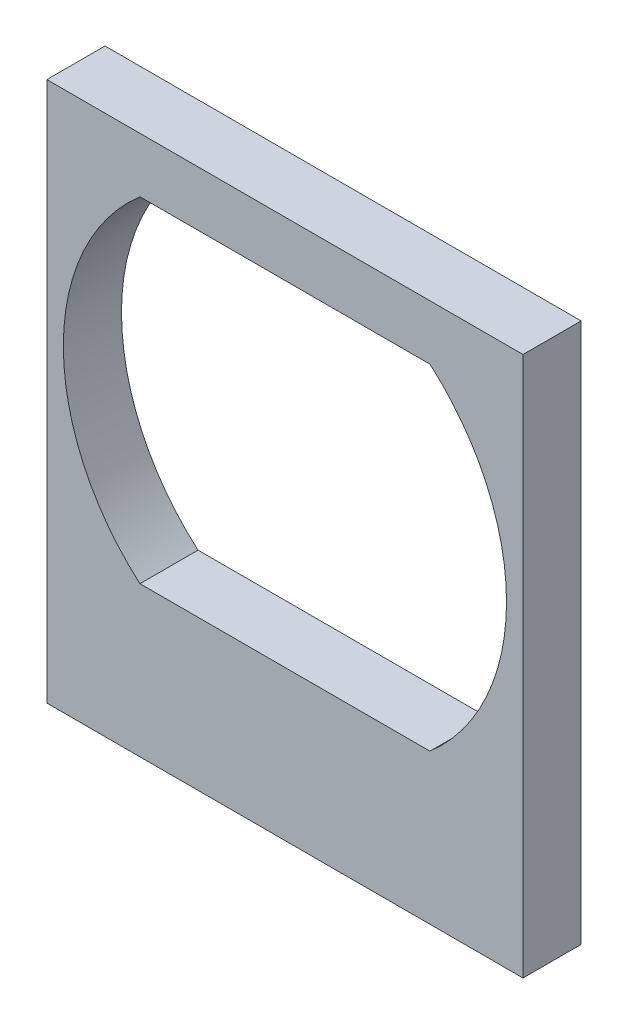
SolidWorks part; units mm, degrees
ref_plane "Front Plane" through (0, 0, 0) normal (1, 0, 0) x (0, 1, 0)
ref_plane "Top Plane" through (0, 0, 0) normal (0, 0, 1) x (0, 1, 0)
ref_plane "Right Plane" through (0, 0, 0) normal (0, 1, 0) x (-1, 0, 0)
sketch "Sketch1" plane through (0, 0, 0) normal (0, 0, 1) x (0, 1, 0)
  line L2 (-9.15, 7.9175) -> (-9.15, -7.9175)
  line L4 (9.15, 7.9175) -> (9.15, -7.9175)
  arc A0 (9.15, 7.9175) -> (-9.15, 7.9175) centre (0, 0) ccw
  arc A1 (-9.15, -7.9175) -> (9.15, -7.9175) centre (0, 0) ccw
  circle A2 centre (0, 0) radius 1.03 construction
  point P7 (9.15, 0)
  dimension "D3" = 24.2
  dimension "D2" = 2.06
  dimension "D1" = 18.3
sketch "Sketch2" plane through (0, 0, 0) normal (0, 0, 1) x (0, 1, 0)
  line L1 (-17.337, 13) -> (12.15, 13)
  line L2 (-17.337, 13) -> (-17.337, -13)
  line L3 (-17.337, -13) -> (12.15, -13)
  line L4 (12.15, 13) -> (12.15, -13)
  line L5 (9.15, 7.9175) -> (9.15, -7.9175) construction
  point P6 (12.15, 0)
  dimension "D1" = 26
  dimension "D2" = 3
  dimension "D3" = 17.337
extrude "Boss-Extrude1" add sketch "Sketch2" along normal blind 3.175
extrude "Cut-Extrude1" cut sketch "Sketch1" along normal through all
hole_wizard "Tap Drill for M3x0.5 Tap1" positions "Sketch3" profile "Sketch4" hole size "M3x0.5" standard "ANSI Metric"
sketch "Sketch3" plane through (0, -17.337, 0) normal (0, -1, 0) x (-1, 0, 0)
  line L0 (-7.5, -1.5875) -> (7.5, -1.5875) construction
  line L2 (13, 0) -> (-13, 0) construction
  line L3 (13, -3.175) -> (-13, -3.175) construction
  point P0 (-7.5, -1.5875)
  point P2 (7.5, -1.5875)
  point P9 (0, -1.5875)
  dimension "D1" = 15
sketch "Sketch4" plane through (7.5, -17.337, 1.5875) normal (1, 0, 0) x (0, 0, -1)
  line L0 (0, 0) -> (0, 6.7511)
  line L1 (0, 6.7511) -> (1.25, 6)
  line L2 (1.25, 6) -> (1.25, 0.025)
  line L3 (1.25, 0.025) -> (1.275, 0)
  line L5 (1.275, 0) -> (0, 0)
  line L6 (-1.25, 0.025) -> (-1.275, 0) construction
  line L10 (0, 6.7511) -> (-1.25, 6) construction
  line L11 (0, -6.35) -> (0, 107.95) construction
  dimension "Hole Dia." = 2.5
  dimension "Hole Depth" = 6
  dimension "Near C'Sink Dia." = 2.55
  dimension "Near C'Sink Angle" = 90
  dimension "Drill Angle" = 118
